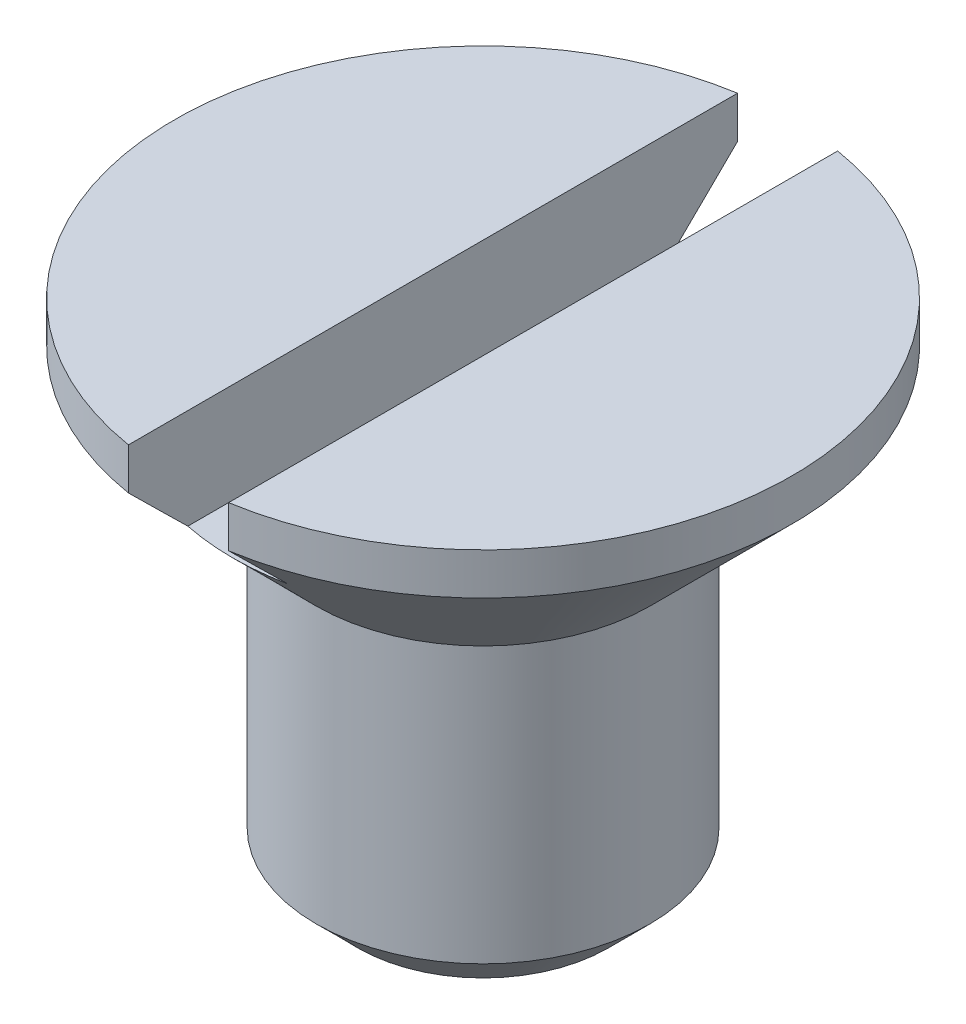
SolidWorks part; units mm, degrees
ref_plane "Спереди" through (0, 0, 0) normal (0, 0, 1) x (1, 0, 0)
ref_plane "Сверху" through (0, 0, 0) normal (0, 1, 0) x (1, 0, 0)
ref_plane "Справа" through (0, 0, 0) normal (1, 0, 0) x (0, 0, -1)
sketch "Эскиз1" plane through (0, 0, 0) normal (0, 0, 1) x (1, 0, 0)
  line L0 (0, 0) -> (-1.5, 0)
  line L1 (-1.5, 0) -> (-2, 0.5)
  line L2 (-2, 0.5) -> (-2, 3.8)
  line L3 (-2, 3.8) -> (-3.7, 5.5)
  line L4 (-3.7, 5.5) -> (-3.7, 6)
  line L5 (-3.7, 6) -> (0, 6)
  line L6 (0, 6) -> (0, 0)
  dimension "D1" = 2
  dimension "D2" = 45
  dimension "D3" = 1.5
  dimension "D4" = 6
  dimension "D5" = 45
  dimension "D6" = 2.2
  dimension "D7" = 3.7
revolve "Повернуть1" add sketch "Эскиз1" angle 360 about L6
sketch "Эскиз2" plane through (0, 0, 0) normal (0, 0, 1) x (1, 0, 0)
  line L0 (0, 0) -> (0, 6) construction
  line L1 (3.7, 6) -> (-3.7, 6) construction
  line L3 (-0.6, 6) -> (0.6, 6)
  line L4 (-0.6, 6) -> (-0.6, 4.8)
  line L5 (-0.6, 4.8) -> (0.6, 4.8)
  line L6 (0.6, 6) -> (0.6, 4.8)
  dimension "D1" = 1.2
  dimension "D2" = 1.2
extrude "Вырез-Вытянуть1" cut sketch "Эскиз2" against normal through all and the other way through all
